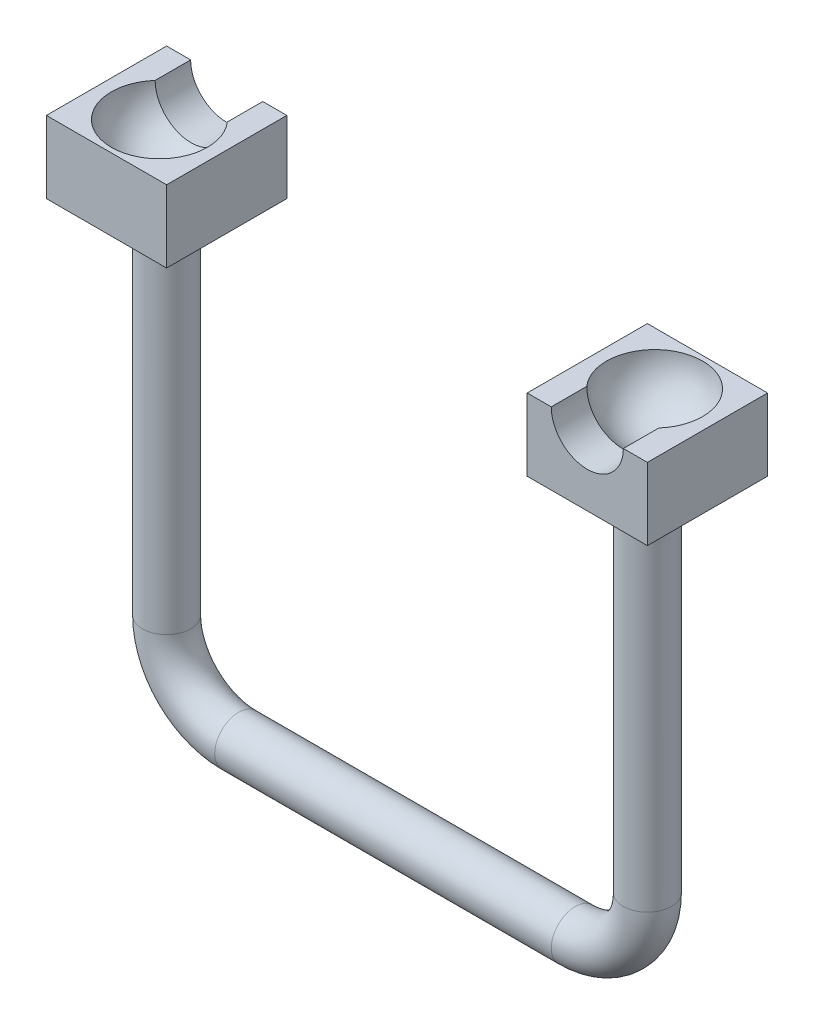
SolidWorks part; units mm, degrees
ref_plane "Front Plane" through (0, 0, 0) normal (0, 0, 1) x (1, 0, 0)
ref_plane "Top Plane" through (0, 0, 0) normal (0, 1, 0) x (1, 0, 0)
ref_plane "Right Plane" through (0, 0, 0) normal (1, 0, 0) x (0, 0, -1)
sketch "Sketch1" plane through (0, 0, 0) normal (0, 0, 1) x (1, 0, 0)
  line L0 (0, 0) -> (0, -75)
  line L1 (15, -90) -> (85, -90)
  line L2 (100, -75) -> (100, 0)
  arc A0 (0, -75) -> (15, -90) centre (15, -75) ccw
  arc A1 (100, -75) -> (85, -90) centre (85, -75) cw
  dimension "D4" = 100
  dimension "D5" = 70
  dimension "D2" = 30
  dimension "D3" = 30
  dimension "D1" = 75
ref_plane "Plane1" through (0, 0, 0) normal (0, 1, 0) x (1, 0, 0)
sketch "Sketch2" plane through (0, 0, 0) normal (0, 1, 0) x (1, 0, 0)
  circle A0 centre (0, 0) radius 5
  dimension "D1" = 10
sweep "Sweep1" add profiles "Sketch2" path "Sketch1"
ref_plane "Plane2" through (0, 0, 0) normal (0, 1, 0) x (1, 0, 0)
sketch "Sketch4" plane through (0, 0, 0) normal (0, 1, 0) x (1, 0, 0)
  line L0 (-13.372, 0) -> (11.7222, 0) construction
  line L1 (0, 12.2632) -> (0, -13.2655) construction
  line L3 (-12.5, -12.5) -> (12.5, -12.5)
  line L4 (-12.5, -12.5) -> (-12.5, 12.5)
  line L5 (-12.5, 12.5) -> (12.5, 12.5)
  line L6 (12.5, -12.5) -> (12.5, 12.5)
  line L7 (-12.5, -12.5) -> (12.5, 12.5) construction
  line L8 (-12.5, 12.5) -> (12.5, -12.5) construction
  point P5 (0, 0)
  dimension "D1" = 25
  dimension "D2" = 25
extrude "Boss-Extrude1" add sketch "Sketch4" along normal blind 15
sketch "Sketch5" plane through (0, 15, 0) normal (0, 1, 0) x (1, 0, 0)
  line L1 (-12.5, 12.5) -> (-12.5, -12.5) construction
  line L2 (0, 8.5) -> (0, -11.5)
  line L3 (-12.5, -12.5) -> (12.5, -12.5) construction
  arc A0 (0, -11.5) -> (0, 8.5) centre (0, -1.5) ccw
  dimension "D1" = 20
  dimension "D3" = 12.5
  dimension "D2" = 11
revolve "Cut-Revolve1" cut sketch "Sketch5" angle 360 about L2
sketch "Sketch7" plane through (0, 0, -12.5) normal (0, 0, -1) x (-1, 0, 0)
  line L0 (-12.5, 15) -> (12.5, 15) construction
  circle A0 centre (0, 15) radius 7.5
  dimension "D1" = 15
extrude "Cut-Extrude2" cut sketch "Sketch7" against normal blind 15
ref_plane "Plane7" through (0, 0, 0) normal (0, 1, 0) x (1, 0, 0)
sketch "Sketch15" plane through (0, 0, 0) normal (0, 1, 0) x (1, 0, 0)
  line L0 (95, 0) -> (105, 0) construction
  line L2 (87.5, -12.5) -> (112.5, -12.5)
  line L3 (87.5, -12.5) -> (87.5, 12.5)
  line L4 (87.5, 12.5) -> (112.5, 12.5)
  line L5 (112.5, -12.5) -> (112.5, 12.5)
  line L6 (87.5, -12.5) -> (112.5, 12.5) construction
  line L7 (87.5, 12.5) -> (112.5, -12.5) construction
  circle A0 centre (100, 0) radius 5 construction
  circle A1 centre (100, 0) radius 5 construction
  point P7 (100, 0)
  dimension "D1" = 25
  dimension "D2" = 25
extrude "Boss-Extrude3" add sketch "Sketch15" along normal blind 15
sketch "Sketch16" plane through (0, 15, 0) normal (0, 1, 0) x (1, 0, 0)
  line L0 (87.5, 12.5) -> (87.5, -12.5) construction
  line L1 (112.5, 12.5) -> (87.5, 12.5) construction
  line L2 (100, 11.5) -> (100, -8.5)
  arc A0 (100, -8.5) -> (100, 11.5) centre (100, 1.5) ccw
  dimension "D1" = 12.5
  dimension "D2" = 20
  dimension "D3" = 11
revolve "Cut-Revolve2" cut sketch "Sketch16" angle 360 about L2
sketch "Sketch17" plane through (0, 0, 12.5) normal (0, 0, 1) x (1, 0, 0)
  line L0 (87.5, 15) -> (112.5, 15) construction
  circle A0 centre (100, 15) radius 7.5
  dimension "D1" = 15
extrude "Cut-Extrude3" cut sketch "Sketch17" against normal blind 15
